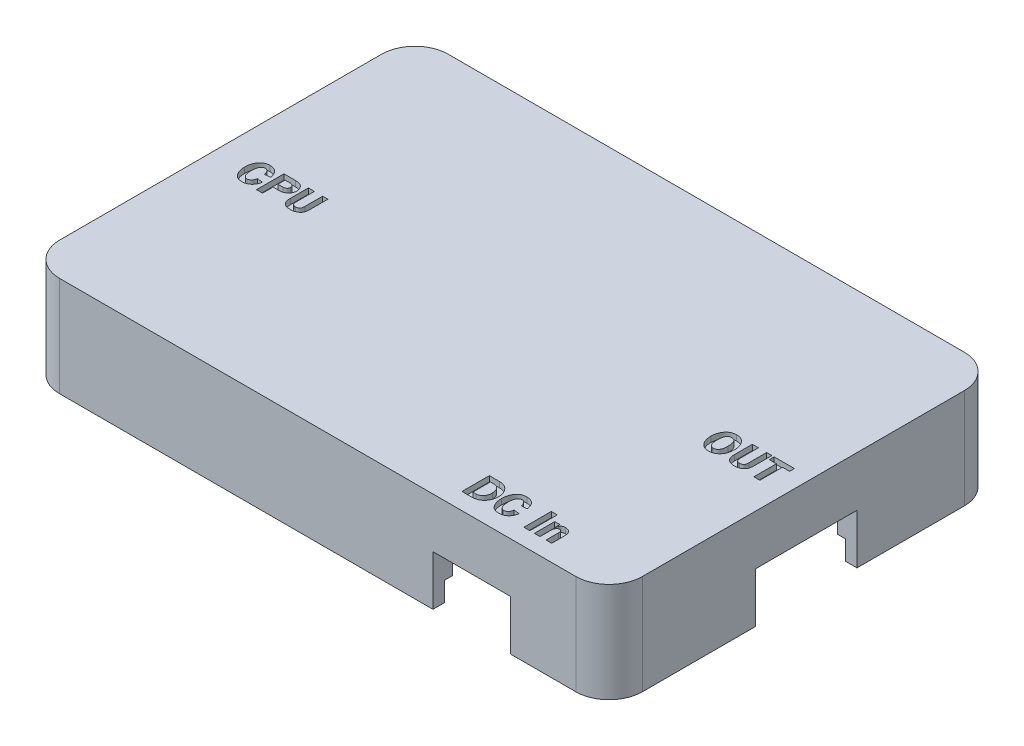
SolidWorks part; units mm, degrees
ref_plane "Front Plane" through (0, 0, 0) normal (0, 0, 1) x (1, 0, 0)
ref_plane "Top Plane" through (0, 0, 0) normal (0, 1, 0) x (1, 0, 0)
ref_plane "Right Plane" through (0, 0, 0) normal (1, 0, 0) x (0, 0, -1)
sketch "Sketch1" plane through (0, 0, 0) normal (0, 1, 0) x (1, 0, 0)
  line L1 (-52.5, 35) -> (52.5, 35)
  line L2 (-52.5, 35) -> (-52.5, -35)
  line L3 (-52.5, -35) -> (52.5, -35)
  line L4 (52.5, 35) -> (52.5, -35)
  line L5 (-52.5, 35) -> (52.5, -35) construction
  line L6 (-52.5, -35) -> (52.5, 35) construction
  point P0 (0, 0)
  dimension "D1" = 105
  dimension "D2" = 70
extrude "Boss-Extrude1" add sketch "Sketch1" along normal blind 15
sketch "Sketch3" plane through (0, 15, 0) normal (0, 1, 0) x (1, 0, 0)
  line L0 (52.5, -35) -> (52.5, 35) construction
  line L1 (49, -31.5) -> (-49, -31.5)
  line L2 (49, -31.5) -> (49, 31.5)
  line L3 (49, 31.5) -> (-49, 31.5)
  line L4 (-49, -31.5) -> (-49, 31.5)
  line L5 (49, -31.5) -> (-49, 31.5) construction
  line L6 (49, 31.5) -> (-49, -31.5) construction
  line L7 (-52.5, -35) -> (52.5, -35) construction
  point P0 (0, 0)
  dimension "D1" = 3.5
  dimension "D2" = 3.5
extrude "Cut-Extrude1" cut sketch "Sketch3" against normal blind 12
fillet "Fillet1" radius 6 8 edges at (-52.5, 7.5, -35) (-52.5, 7.5, 35) (52.5, 7.5, -35) (52.5, 7.5, 35) (49, 9, -31.5) (-49, 9, -31.5) (-49, 9, 31.5) (49, 9, 31.5)
sketch "Sketch4" plane through (0, 3, 0) normal (0, 1, 0) x (1, 0, 0)
  line L0 (-43, -31.5) -> (43, -31.5) construction
  line L1 (49, -25.5) -> (49, 25.5) construction
  circle A0 centre (40, -22.5) radius 3.5
  circle A1 centre (40, 19.2) radius 3.5
  circle A2 centre (-36.1, -22.5) radius 3.5
  circle A3 centre (-36.1, 19.2) radius 3.5
  dimension "D5" = 7
  dimension "D6" = 76.1
  dimension "D1" = 41.7
  dimension "D2" = 9
  dimension "D3" = 76.1
  dimension "D4" = 9
  dimension "D7" = 41.7
extrude "Boss-Extrude2" [suppressed] add sketch "Sketch4" along normal blind 5
sketch "Sketch5" [suppressed] plane through (0, 8, 0) normal (0, 1, 0) x (1, 0, 0)
  circle A0 centre (-36.1, 19.2) radius 1
  circle A1 centre (-36.1, -22.5) radius 1
  circle A2 centre (40, -22.5) radius 1
  circle A3 centre (40, 19.0603) radius 1
  dimension "D1" = 2
extrude "Cut-Extrude2" [suppressed] cut sketch "Sketch5" against normal blind 8
sketch "Sketch6" plane through (0, 15, 0) normal (0, 1, 0) x (1, 0, 0)
  line L0 (49, -25.5) -> (49, 25.5) construction
  line L1 (49, 9.66) -> (52.5, 9.66)
  line L2 (49, 9.66) -> (49, -8.64)
  line L3 (49, -8.64) -> (52.5, -8.64)
  line L4 (52.5, 9.66) -> (52.5, -8.64)
  line L5 (52.5, -29) -> (52.5, 29) construction
  line L6 (-46.5, -35) -> (46.5, -35) construction
  line L7 (34.76, -35) -> (20.76, -35)
  line L8 (34.76, -35) -> (34.76, -31.5)
  line L9 (34.76, -31.5) -> (20.76, -31.5)
  line L10 (20.76, -35) -> (20.76, -31.5)
  line L11 (-43, -31.5) -> (43, -31.5) construction
  line L12 (-52.5, 29) -> (-52.5, -29) construction
  line L13 (-52.5, 10) -> (-49, 10)
  line L14 (-52.5, 10) -> (-52.5, -10)
  line L15 (-52.5, -10) -> (-49, -10)
  line L16 (-49, 10) -> (-49, -10)
  line L17 (-49, 25.5) -> (-49, -25.5) construction
  dimension "D1" = 14
  dimension "D2" = 20
  dimension "D3" = 25
  dimension "D4" = 14.24
  dimension "D5" = 22.86
  dimension "D6" = 18.3
extrude "Cut-Extrude3" cut sketch "Sketch6" against normal blind 26
sketch "Sketch9" plane through (0, 3, 0) normal (0, 1, 0) x (1, 0, 0)
  line L1 (-43, 31.5) -> (43, 31.5)
  line L2 (-49, 25.5) -> (-49, -25.5)
  line L3 (-43, -31.5) -> (43, -31.5)
  line L4 (49, 25.5) -> (49, -25.5)
  line L5 (-49, 31.5) -> (49, -31.5) construction
  line L6 (-49, -31.5) -> (49, 31.5) construction
  line L7 (-43, -31.5) -> (20.76, -31.5) construction
  arc A0 (-43, 31.5) -> (-49, 25.5) centre (-43, 25.5) ccw
  arc A1 (43, 31.5) -> (49, 25.5) centre (43, 25.5) cw
  arc A2 (43, -31.5) -> (49, -25.5) centre (43, -25.5) ccw
  arc A3 (-49, -25.5) -> (-43, -31.5) centre (-43, -25.5) ccw
  point P0 (0, 0)
  dimension "D3" = 6
  dimension "D2" = 0
extrude "Cut-Extrude4" cut sketch "Sketch9" against normal blind 10
sketch "Sketch10" plane through (0, 15, 0) normal (0, 1, 0) x (1, 0, 0)
  line L0 (-52.5, -10) -> (-52.5, -29) construction
  line L1 (-46.5, 35) -> (46.5, 35)
  line L2 (-52.5, 29) -> (-52.5, -29)
  line L3 (-46.5, -35) -> (46.5, -35)
  line L4 (52.5, 29) -> (52.5, -29)
  line L5 (-52.5, 35) -> (52.5, -35) construction
  line L6 (-52.5, -35) -> (52.5, 35) construction
  line L7 (-46.5, -35) -> (20.76, -35) construction
  arc A0 (46.5, -35) -> (52.5, -29) centre (46.5, -29) ccw
  arc A1 (46.5, 35) -> (52.5, 29) centre (46.5, 29) cw
  arc A2 (-46.5, 35) -> (-52.5, 29) centre (-46.5, 29) ccw
  arc A3 (-52.5, -29) -> (-46.5, -35) centre (-46.5, -29) ccw
  point P0 (0, 0)
  dimension "D3" = 6
  dimension "D1" = 0
  dimension "D2" = 0
extrude "Boss-Extrude3" add sketch "Sketch10" along normal blind 3
sketch "Sketch11" plane through (0, 0, 0) normal (0, -1, 0) x (-1, 0, 0)
  line L0 (-46.5, 35) -> (46.5, 35) construction
  line L1 (-44.4, 32.9) -> (44.4, 32.9)
  line L2 (-50.4, 26.9) -> (-50.4, -26.9)
  line L3 (-44.4, -32.9) -> (44.4, -32.9)
  line L4 (50.4, 26.9) -> (50.4, -26.9)
  line L5 (-50.4, 32.9) -> (50.4, -32.9) construction
  line L6 (-50.4, -32.9) -> (50.4, 32.9) construction
  line L7 (-52.5, -29) -> (-52.5, -8.64) construction
  arc A0 (44.4, -32.9) -> (50.4, -26.9) centre (44.4, -26.9) ccw
  arc A1 (44.4, 32.9) -> (50.4, 26.9) centre (44.4, 26.9) cw
  arc A2 (-44.4, 32.9) -> (-50.4, 26.9) centre (-44.4, 26.9) ccw
  arc A3 (-50.4, -26.9) -> (-44.4, -32.9) centre (-44.4, -26.9) ccw
  point P0 (0, 0)
  dimension "D3" = 6
  dimension "D1" = 2.1
  dimension "D2" = 2.1
extrude "Cut-Extrude5" cut sketch "Sketch11" against normal blind 3.5
sketch "Sketch12" plane through (0, 15, 0) normal (0, -1, 0) x (-1, 0, 0)
  line L1 (-52.5, 9.66) -> (-49, 9.66)
  line L2 (-52.5, 9.66) -> (-52.5, -8.64)
  line L3 (-52.5, -8.64) -> (-49, -8.64)
  line L4 (-49, 9.66) -> (-49, -8.64)
  line L5 (-20.76, -35) -> (-34.76, -35)
  line L6 (-20.76, -35) -> (-20.76, -31.5)
  line L7 (-20.76, -31.5) -> (-34.76, -31.5)
  line L8 (-34.76, -35) -> (-34.76, -31.5)
  line L9 (49, -10) -> (52.5, -10)
  line L10 (49, -10) -> (49, 10)
  line L11 (49, 10) -> (52.5, 10)
  line L12 (52.5, -10) -> (52.5, 10)
extrude "Boss-Extrude4" add sketch "Sketch12" along normal blind 6
sketch "Sketch13" plane through (0, 18, 0) normal (0, 1, 0) x (1, 0, 0)
  line L0 (-52.5, 29) -> (-52.5, -29) construction
  line L1 (-52.5, -0.4066) -> (52.5, -0.4066) construction
  line L2 (52.5, -29) -> (52.5, 29) construction
  line L3 (-46.5, -35) -> (46.5, -35) construction
  text T0 "<b>CPU</b>" font "Franklin Gothic Medium" height in points 20
  text T1 "DC In" font "Franklin Gothic Medium" height in points 20
  text T2 "OUT" font "Franklin Gothic Medium" height in points 20
  point P9 (0, -35)
  dimension "D1" = 5
  dimension "D2" = 3
  dimension "D3" = 3
  dimension "D4" = 30
  dimension "D5" = 16
  dimension "D6" = 3
extrude "Cut-Extrude6" cut sketch "Sketch13" against normal blind 1
equation "\"D2@Sketch3\"=\"D1@Sketch3\""
equation "\"D4@Sketch4\"=\"D2@Sketch4\""
equation "\"D6@Sketch4\"=\"D3@Sketch4\""
equation "\"D7@Sketch4\"=\"D1@Sketch4\""
